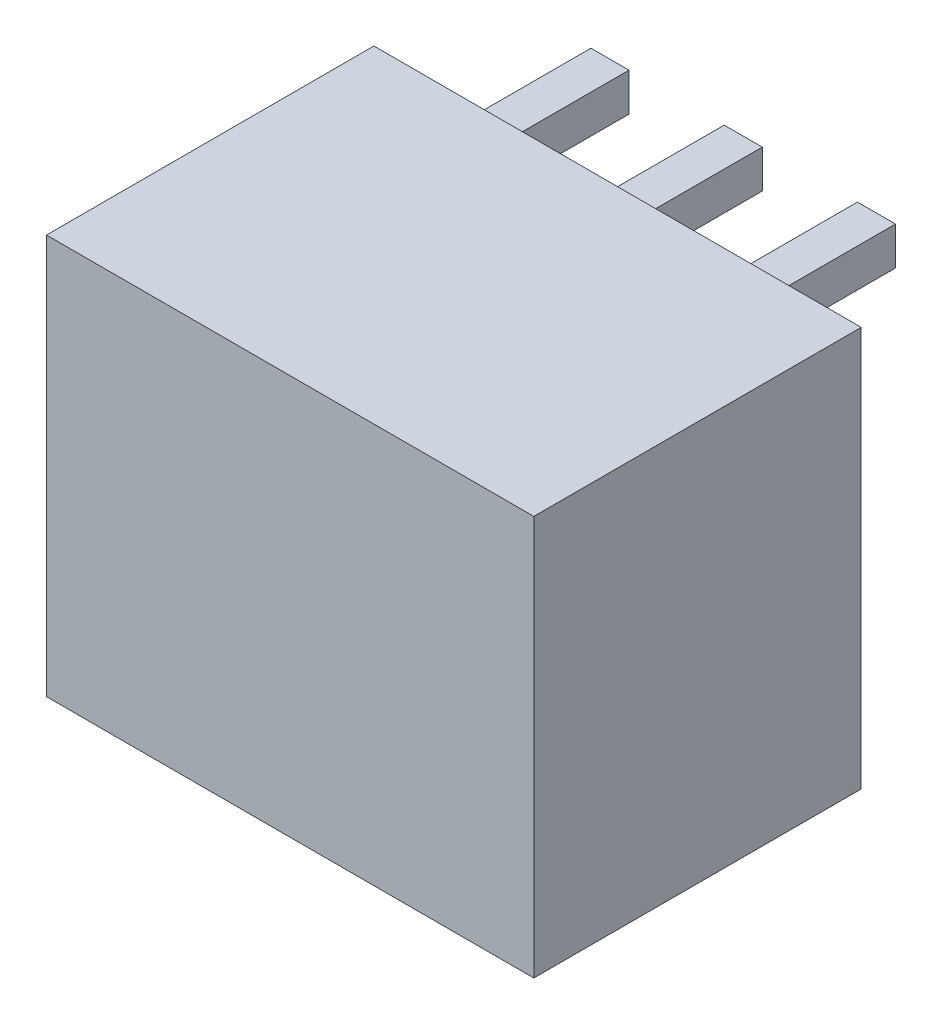
SolidWorks part; units mm, degrees
ref_plane "Спереди" through (0, 0, 0) normal (0, 0, 1) x (1, 0, 0)
ref_plane "Сверху" through (0, 0, 0) normal (0, 1, 0) x (1, 0, 0)
ref_plane "Справа" through (0, 0, 0) normal (1, 0, 0) x (0, 0, -1)
sketch "Эскиз1" plane through (0, 0, 0) normal (0, 0, 1) x (1, 0, 0)
  line L1 (-6.4, -5.25) -> (6.4, -5.25)
  line L2 (-6.4, -5.25) -> (-6.4, 5.25)
  line L3 (-6.4, 5.25) -> (6.4, 5.25)
  line L4 (6.4, -5.25) -> (6.4, 5.25)
  line L5 (-6.4, -5.25) -> (6.4, 5.25) construction
  line L6 (-6.4, 5.25) -> (6.4, -5.25) construction
  point P0 (0, 0)
  dimension "D1" = 12.8
  dimension "D2" = 10.5
extrude "Бобышка-Вытянуть1" add sketch "Эскиз1" along normal blind 8.6
sketch "Эскиз2" plane through (0, -5.25, 0) normal (0, -1, 0) x (1, 0, 0)
  line L0 (-5.4, 6.6) -> (5.4, 6.6)
  line L1 (5.4, 6.6) -> (5.4, 0.2)
  line L2 (5.4, 0.2) -> (3.2, 0.2)
  line L3 (3.2, 0.2) -> (3.2, 1.8)
  line L4 (3.2, 1.8) -> (-1.6, 1.8)
  line L5 (-1.6, 1.8) -> (-1.6, 0.2)
  line L6 (-1.6, 0.2) -> (-3.8, 0.2)
  line L7 (-5.4, 6.6) -> (-5.4, 1.8)
  line L8 (-5.4, 1.8) -> (-3.8, 1.8)
  line L9 (-3.8, 1.8) -> (-3.8, 0.2)
  line L10 (6.4, 8.6) -> (6.4, 0) construction
  line L11 (-6.4, 8.6) -> (-6.4, 0) construction
  line L12 (-6.4, 8.6) -> (6.4, 8.6) construction
  dimension "D1" = 4.8
  dimension "D2" = 6.4
  dimension "D3" = 2.2
  dimension "D4" = 2.2
  dimension "D5" = 3.2
  dimension "D6" = 4.8
  dimension "D7" = 1
  dimension "D8" = 2
extrude "Вырез-Вытянуть1" cut sketch "Эскиз2" against normal blind 7
sketch "Эскиз3" plane through (0, 0, 0) normal (0, 0, -1) x (-1, 0, 0)
  line L0 (6.4, -5.25) -> (-6.4, -5.25) construction
  line L1 (4, 4.75) -> (3, 4.75)
  line L2 (4, 4.75) -> (4, 3.75)
  line L3 (4, 3.75) -> (3, 3.75)
  line L4 (3, 4.75) -> (3, 3.75)
  line L5 (4, 4.75) -> (3, 3.75) construction
  line L6 (4, 3.75) -> (3, 4.75) construction
  line L7 (6.4, 5.25) -> (6.4, -5.25) construction
  point P0 (3.5, 4.25)
  dimension "D1" = 1
  dimension "D2" = 9.5
  dimension "D3" = 2.9
extrude "Бобышка-Вытянуть2" add sketch "Эскиз3" along normal blind 3.6 and the other way blind 5
chamfer "Фаска1" distance 0.3 distance2 0.3 4 edges at (-3, 4.25, -3.6) (-3.5, 3.75, -3.6) (-4, 4.25, -3.6) (-3.5, 4.75, -3.6)
pattern_linear "Линейный массив1" count 3 spacing 3.5 along (1, 0, 0) of "Бобышка-Вытянуть2", "Фаска1"
equation "\"N\"= 3"
equation "\"D1@Эскиз1\"= ( \"N\" - 1 ) * 3.5 + 5.8"
equation "\"D1@Линейный массив1\"=\"N\""
